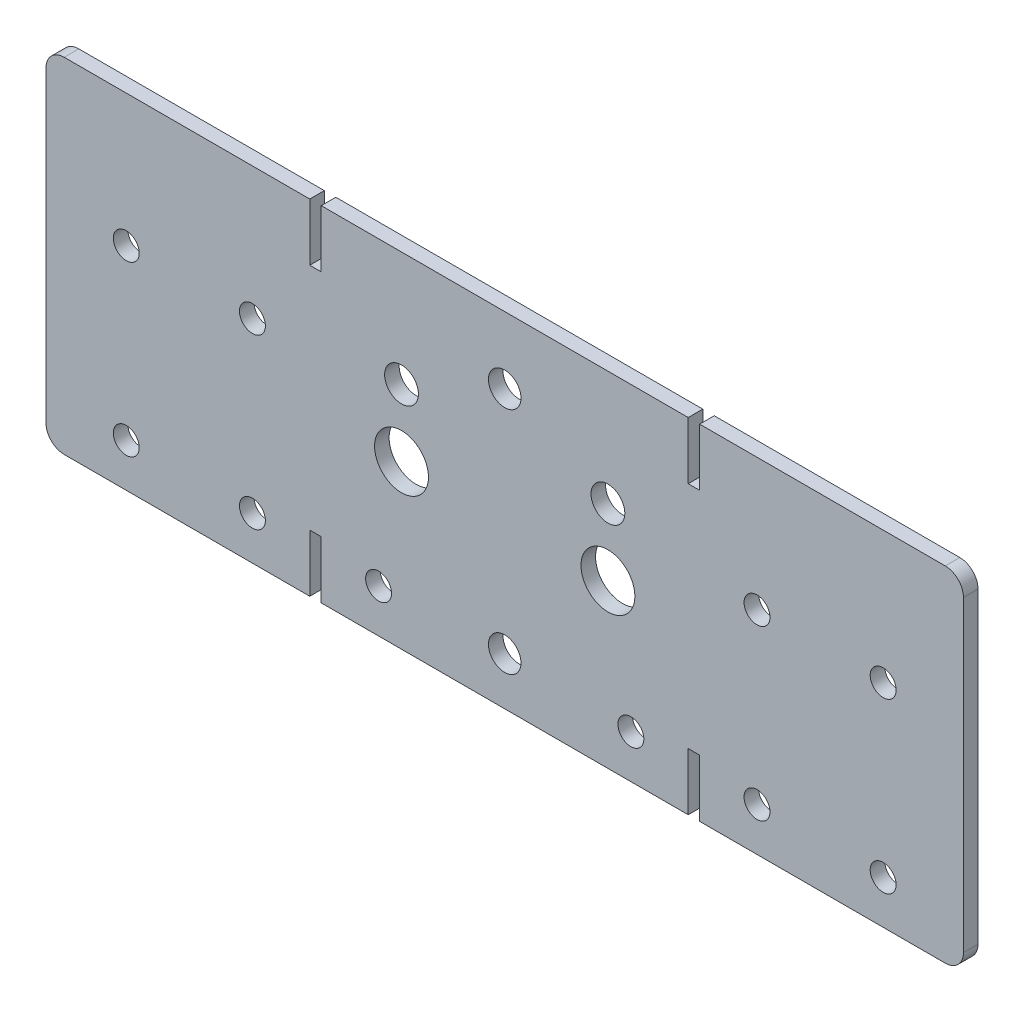
SolidWorks part; units mm, degrees
ref_plane "Front Plane" through (0, 0, 0) normal (0, 0, 1) x (1, 0, 0)
ref_plane "Top Plane" through (0, 0, 0) normal (0, 1, 0) x (1, 0, 0)
ref_plane "Right Plane" through (0, 0, 0) normal (1, 0, 0) x (0, 0, -1)
sketch "Sketch1" plane through (0, 0, 0) normal (0, 0, 1) x (1, 0, 0)
  line L0 (13, -14.7) -> (23, -14.7) construction
  line L1 (0, 0) -> (80, 0)
  line L2 (0, 0) -> (0, -30)
  line L3 (0, -30) -> (80, -30)
  line L4 (80, 0) -> (80, -30)
  line L5 (2, -2) -> (12, -2) construction
  line L6 (2, -2) -> (2, -14.7) construction
  line L7 (2, -14.7) -> (12, -14.7) construction
  line L8 (12, -2) -> (12, -14.7) construction
  line L9 (23, -2) -> (23, -14.7) construction
  line L10 (13, -2) -> (23, -2) construction
  line L11 (13, -2) -> (13, -14.7) construction
  line L12 (24, -14.7) -> (34, -14.7) construction
  line L13 (34, -2) -> (34, -14.7) construction
  line L14 (24, -2) -> (34, -2) construction
  line L15 (24, -2) -> (24, -14.7) construction
  line L16 (35, -14.7) -> (45, -14.7) construction
  line L17 (45, -2) -> (45, -14.7) construction
  line L18 (35, -2) -> (45, -2) construction
  line L19 (35, -2) -> (35, -14.7) construction
  line L20 (46, -14.7) -> (56, -14.7) construction
  line L21 (56, -2) -> (56, -14.7) construction
  line L22 (46, -2) -> (56, -2) construction
  line L23 (46, -2) -> (46, -14.7) construction
  line L24 (57, -14.7) -> (67, -14.7) construction
  line L25 (67, -2) -> (67, -14.7) construction
  line L26 (57, -2) -> (67, -2) construction
  line L27 (57, -2) -> (57, -14.7) construction
  line L28 (68, -14.7) -> (78, -14.7) construction
  line L29 (78, -2) -> (78, -14.7) construction
  line L30 (68, -2) -> (78, -2) construction
  line L31 (68, -2) -> (68, -14.7) construction
  line L32 (13, -29.4) -> (23, -29.4) construction
  line L33 (23, -16.7) -> (23, -29.4) construction
  line L34 (13, -16.7) -> (23, -16.7) construction
  line L35 (13, -16.7) -> (13, -29.4) construction
  line L36 (24, -29.4) -> (34, -29.4) construction
  line L37 (34, -16.7) -> (34, -29.4) construction
  line L38 (24, -16.7) -> (34, -16.7) construction
  line L39 (24, -16.7) -> (24, -29.4) construction
  line L40 (35, -29.4) -> (45, -29.4) construction
  line L41 (45, -16.7) -> (45, -29.4) construction
  line L42 (35, -16.7) -> (45, -16.7) construction
  line L43 (35, -16.7) -> (35, -29.4) construction
  line L44 (46, -29.4) -> (56, -29.4) construction
  line L45 (56, -16.7) -> (56, -29.4) construction
  line L46 (46, -16.7) -> (56, -16.7) construction
  line L47 (46, -16.7) -> (46, -29.4) construction
  line L48 (57, -29.4) -> (67, -29.4) construction
  line L49 (67, -16.7) -> (67, -29.4) construction
  line L50 (57, -16.7) -> (67, -16.7) construction
  line L51 (57, -16.7) -> (57, -29.4) construction
  line L52 (68, -29.4) -> (78, -29.4) construction
  line L53 (78, -16.7) -> (78, -29.4) construction
  line L54 (68, -16.7) -> (78, -16.7) construction
  line L55 (68, -16.7) -> (68, -29.4) construction
  line L56 (2, -29.4) -> (12, -29.4) construction
  line L57 (12, -16.7) -> (12, -29.4) construction
  line L58 (2, -16.7) -> (12, -16.7) construction
  line L59 (2, -16.7) -> (2, -29.4) construction
  line L60 (24, 0) -> (24, -5)
  line L61 (24, -5) -> (23, -5)
  line L62 (23, -5) -> (23, 0)
  line L64 (0, -15) -> (80, -15) construction
  line L65 (56, -5) -> (57, -5)
  line L66 (57, -5) -> (57, 0)
  line L67 (56, 0) -> (56, -5)
  line L68 (24, -25) -> (23, -25)
  line L69 (56, -25) -> (57, -25)
  line L70 (57, -25) -> (57, -30)
  line L71 (56, -30) -> (56, -25)
  line L72 (23, -25) -> (23, -30)
  line L73 (24, -30) -> (24, -25)
  line L74 (40, -5.8325) -> (40, -25.8325) construction
  line L75 (35, -30) -> (45, -30)
  line L76 (35, -30) -> (35, -17.3)
  line L77 (35, -17.3) -> (45, -17.3)
  line L78 (45, -30) -> (45, -17.3)
  line L79 (31, -15.8325) -> (49, -15.8325) construction
  circle A0 centre (7, -11.525) radius 1.1303
  circle A1 centre (31, -10) radius 1.4732
  circle A2 centre (49, -10) radius 1.4732
  circle A3 centre (18, -11.525) radius 1.1303
  circle A4 centre (29, -11.525) radius 1.1303 [skipped]
  circle A5 centre (40, -11.525) radius 1.1303 construction
  circle A6 centre (51, -11.525) radius 1.1303 [skipped]
  circle A7 centre (62, -11.525) radius 1.1303
  circle A8 centre (73, -11.525) radius 1.1303
  circle A9 centre (18, -26.225) radius 1.1303
  circle A10 centre (29, -26.225) radius 1.1303
  circle A11 centre (40, -26.225) radius 1.1303 construction
  circle A12 centre (51, -26.225) radius 1.1303
  circle A13 centre (62, -26.225) radius 1.1303
  circle A14 centre (73, -26.225) radius 1.1303
  circle A15 centre (7, -26.225) radius 1.1303
  circle A16 centre (31, -10) radius 2.3241 construction
  circle A17 centre (31, -10) radius 3.6571 construction
  circle A18 centre (40, -5.8325) radius 1.42
  circle A19 centre (40, -25.8325) radius 1.42
  circle A20 centre (49, -15.8325) radius 2.3495
  circle A21 centre (31, -15.8325) radius 2.3495
  point P11 (7, -14.7)
  point P99 (40, -15.8325)
  point P100 (40, -15.8325)
  point P126 (49, -15.8325)
  point P127 (0, 0)
  dimension "D7" = 2.9464
  dimension "D11" = 2.2606
  dimension "D16" = 4.6482
  dimension "D22" = 2.84
  dimension "D24" = 4.699
  dimension "D1" = 3.175
  dimension "D2" = 12.7
  dimension "D3" = 10
  dimension "D4" = 2
  dimension "D5" = 2
  dimension "D6" = 18
  dimension "D8" = 80
  dimension "D9" = 31
  dimension "D10" = 10
  dimension "D14" = 2
  dimension "D15" = 2
  dimension "D17" = 30
  dimension "D18" = 5
  dimension "D19" = 10
  dimension "D20" = 12.7
  dimension "D21" = 20
  dimension "D23" = 18
  dimension "D12" = 7
  dimension "D13" = 2
extrude "Boss-Extrude1" add sketch "Sketch1" along normal blind 1.27 contours L3 L78 L77 L76 A11 | A11 | A5 | L78 L3 L71 L69 L70 L4 L1 L66 L65 L67 L60 L61 L62 L2 L72 L68 L73 L76 L77 A15 A14 A13 A12 A10 A9 A8 A7 A5 A3 A2 A1 A0
fillet "Fillet1" radius 1.5875 4 edges at (0, -30, 0.635) (0, 0, 0.635) (80, -30, 0.635) (80, 0, 0.635)
equation "\"D9@Sketch1\"=(\"D8@Sketch1\"-\"D6@Sketch1\")/2"
